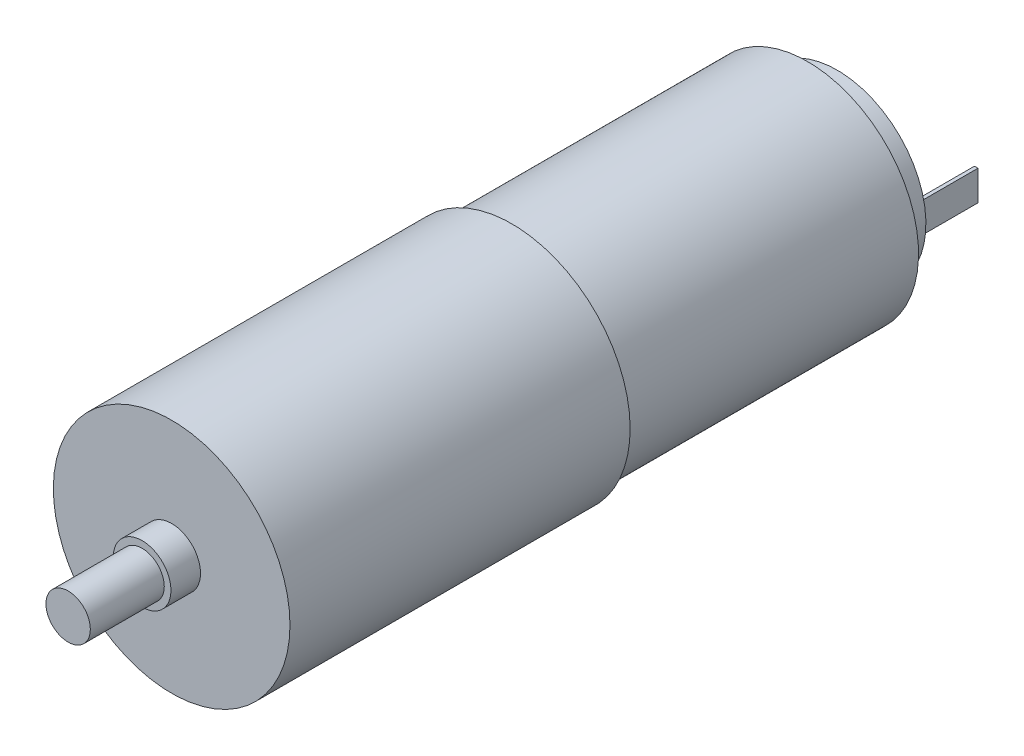
SolidWorks part; units mm, degrees
material "氧化铝"
ref_plane "前视基准面" through (0, 0, 0) normal (0, 0, 1) x (1, 0, 0)
ref_plane "上视基准面" through (0, 0, 0) normal (0, 1, 0) x (1, 0, 0)
ref_plane "右视基准面" through (0, 0, 0) normal (1, 0, 0) x (0, 0, -1)
other "Configuration Table"
sketch "草图1" plane through (0, 0, 0) normal (0, 0, 1) x (1, 0, 0)
  circle A0 centre (0, 0) radius 8
extrude "凸台-拉伸1" add sketch "草图1" along normal blind 23
sketch "草图2" plane through (0, 0, 0) normal (0, 0, -1) x (-1, 0, 0)
  circle A0 centre (0, 0) radius 6
extrude "凸台-拉伸2" add sketch "草图2" along normal blind 22
sketch "草图4" plane through (0, 0, 23) normal (0, 0, 1) x (1, 0, 0)
  circle A0 centre (0, 0) radius 1.95
extrude "凸台-拉伸4" add sketch "草图4" along normal blind 2
sketch "草图5" plane through (0, 0, 0) normal (0, 0, -1) x (-1, 0, 0)
  circle A0 centre (0, 0) radius 7.5
extrude "凸台-拉伸6" add sketch "草图5" along normal blind 20
sketch "草图6" plane through (0, 0, -20) normal (0, 0, -1) x (-1, 0, 0)
  line L0 (0, -6) -> (7.2519, -6)
  line L1 (7.2519, -6) -> (7.2519, -9)
  line L2 (7.2519, -9) -> (-7.0729, -9)
  line L3 (-7.0729, -9) -> (-7.0729, -6)
  line L4 (-7.0729, -6) -> (0, -6)
  circle A0 centre (0, 0) radius 6 construction
  circle A1 centre (0, 0) radius 6 construction
extrude "切除-拉伸2" cut sketch "草图6" against normal blind 25
sketch "草图7" plane through (0, 0, -22) normal (0, 0, -1) x (-1, 0, 0)
  line L1 (-5.521, -1.0147) -> (-5.2823, -1.0147)
  line L2 (-5.521, -1.0147) -> (-5.521, 1.0147)
  line L3 (-5.521, 1.0147) -> (-5.2823, 1.0147)
  line L4 (-5.2823, -1.0147) -> (-5.2823, 1.0147)
  line L5 (-5.521, -1.0147) -> (-5.2823, 1.0147) construction
  line L6 (-5.521, 1.0147) -> (-5.2823, -1.0147) construction
  line L7 (5.2674, -1.0147) -> (5.4763, -1.0147)
  line L8 (5.2674, -1.0147) -> (5.2674, 1.0147)
  line L9 (5.2674, 1.0147) -> (5.4763, 1.0147)
  line L10 (5.4763, -1.0147) -> (5.4763, 1.0147)
  line L11 (5.2674, -1.0147) -> (5.4763, 1.0147) construction
  line L12 (5.2674, 1.0147) -> (5.4763, -1.0147) construction
  point P0 (-5.4016, 0)
  point P5 (5.3718, 0)
extrude "凸台-拉伸7" add sketch "草图7" along normal blind 4
sketch "草图8" plane through (0, 0, 25) normal (0, 0, 1) x (1, 0, 0)
  circle A0 centre (0, 0) radius 1.5
extrude "凸台-拉伸8" add sketch "草图8" along normal blind 5
